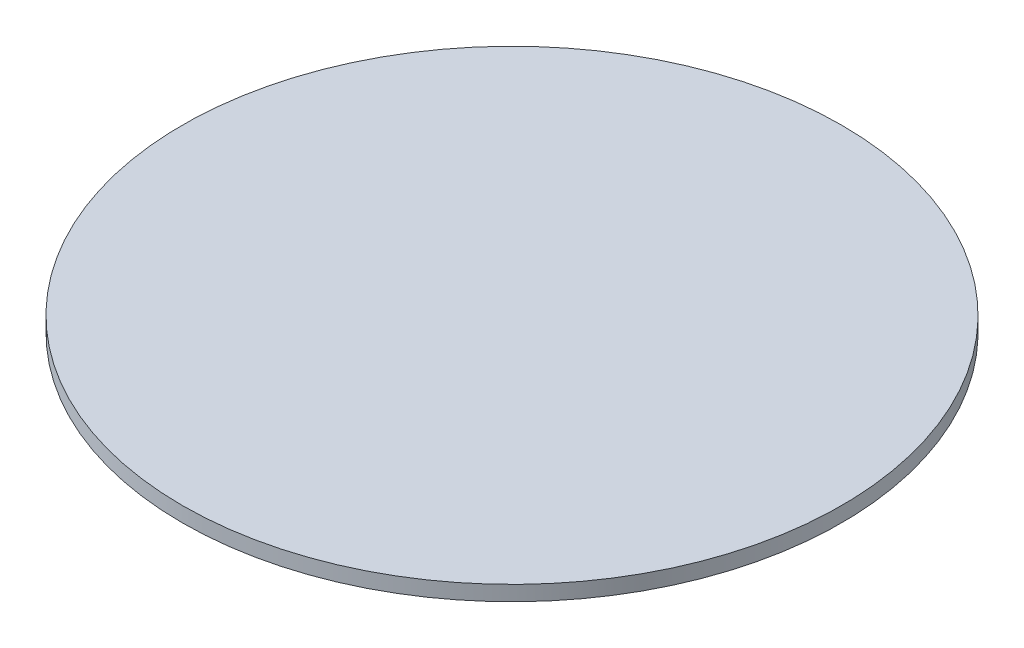
SolidWorks part; units mm, degrees
ref_plane "Front Plane" through (0, 0, 0) normal (0, 0, 1) x (1, 0, 0)
ref_plane "Top Plane" through (0, 0, 0) normal (0, 1, 0) x (1, 0, 0)
ref_plane "Right Plane" through (0, 0, 0) normal (1, 0, 0) x (0, 0, -1)
sketch "Sketch1" plane through (0, 0, 0) normal (0, 1, 0) x (1, 0, 0)
  circle A0 centre (0, 0) radius 55.6628
extrude "Boss-Extrude1" add sketch "Sketch1" along normal blind 2.54
